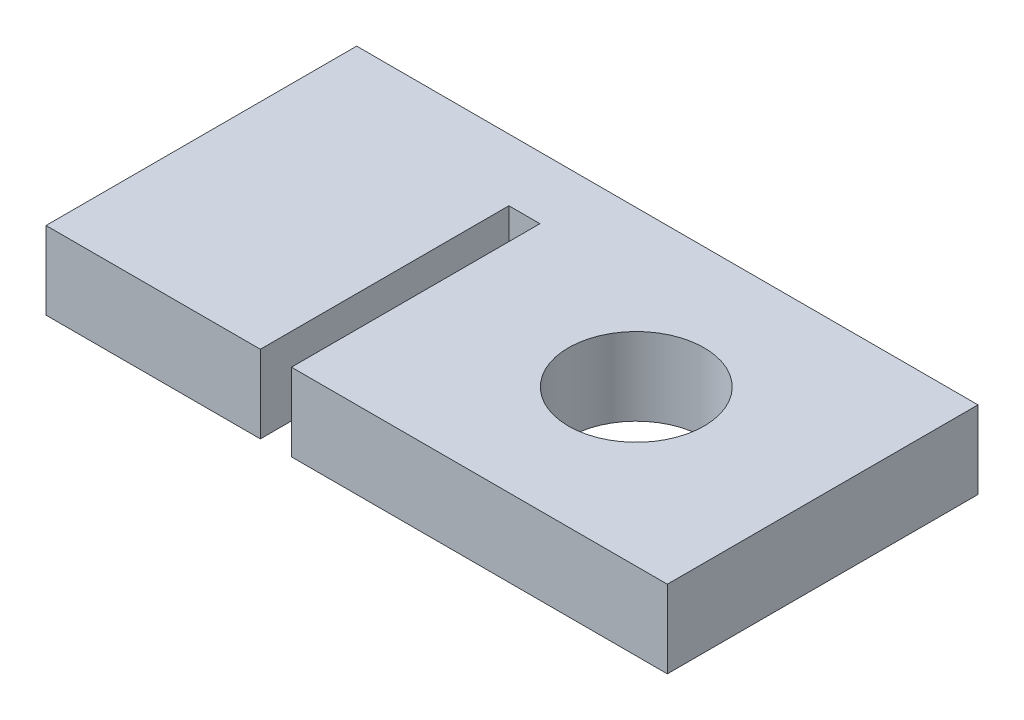
SolidWorks part; units mm, degrees
ref_plane "Front Plane" through (0, 0, 0) normal (0, 0, 1) x (1, 0, 0)
ref_plane "Top Plane" through (0, 0, 0) normal (0, 1, 0) x (1, 0, 0)
ref_plane "Right Plane" through (0, 0, 0) normal (1, 0, 0) x (0, 0, -1)
sketch "Sketch1" plane through (0, 0, 0) normal (0, 1, 0) x (1, 0, 0)
  line L0 (-1.05, -2.5) -> (5, -2.5)
  line L1 (-5, -2.5) -> (-1.55, -2.5)
  line L2 (-5, -2.5) -> (-5, 2.5)
  line L3 (-5, 2.5) -> (5, 2.5)
  line L4 (5, -2.5) -> (5, 2.5)
  line L5 (-5, -2.5) -> (5, 2.5) construction
  line L6 (-5, 2.5) -> (5, -2.5) construction
  line L8 (-1.55, -2.5) -> (-1.55, 1.5)
  line L9 (-1.55, 1.5) -> (-1.05, 1.5)
  line L10 (-1.05, -2.5) -> (-1.05, 1.5)
  point P0 (0, 0)
  dimension "D1" = 5
  dimension "D2" = 10
  dimension "D3" = 4
  dimension "D4" = 0.5
  dimension "D5" = 3.45
extrude "Boss-Extrude1" add sketch "Sketch1" along normal blind 1.25
sketch "Sketch5" plane through (0, 1.25, 0) normal (0, 1, 0) x (1, 0, 0)
  line L0 (5, -2.5) -> (5, 2.5) construction
  circle A0 centre (2, 0) radius 1.0922
  dimension "D1" = 2.1844
  dimension "D2" = 3
extrude "Cut-Extrude1" cut sketch "Sketch5" against normal through all
sketch "Sketch6" plane through (0, 1.25, 0) normal (0, 1, 0) x (1, 0, 0)
  line L3 (-3.275, -2.5) -> (-3.275, 2.5) construction
  line L4 (-5, -2.5) -> (-1.55, -2.5) construction
  line L5 (5, 2.5) -> (-5, 2.5) construction
